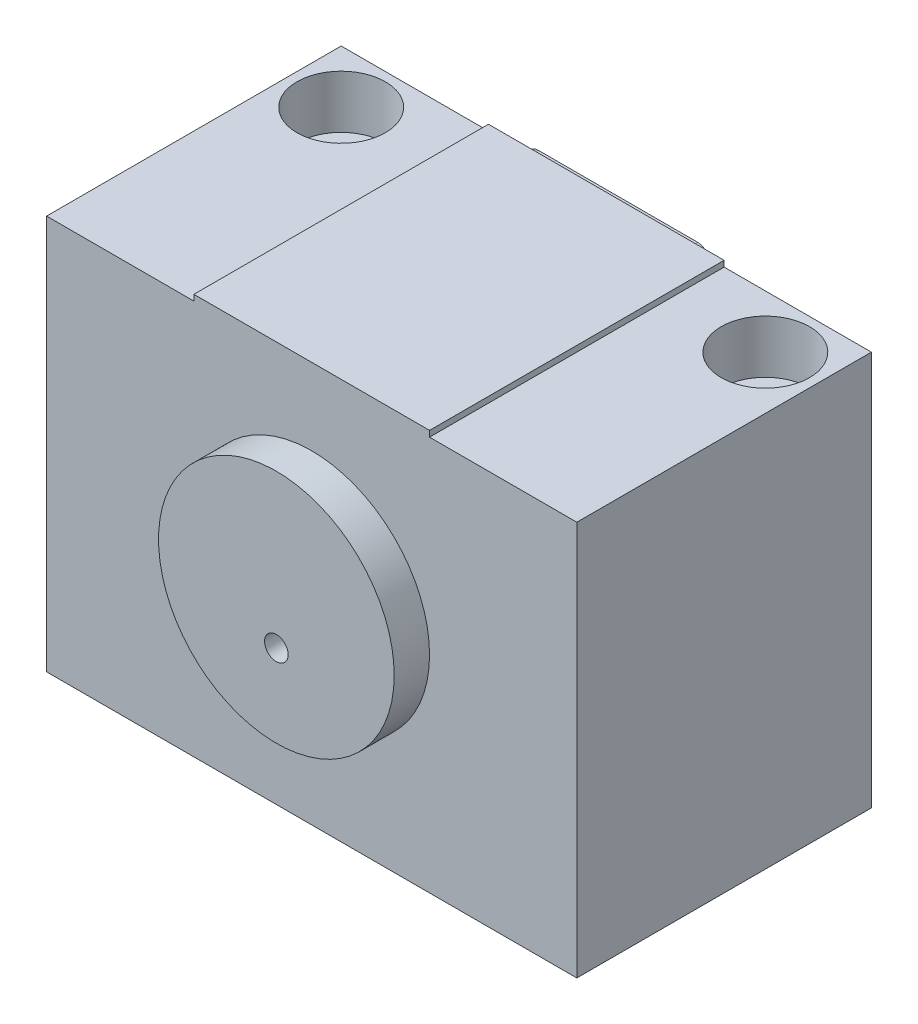
SolidWorks part; units mm, degrees
material "6061-O (SS)"
ref_plane "Plane1" through (0, 0, 0) normal (0, 0, 1) x (1, 0, 0)
ref_plane "Plane2" through (0, 0, 0) normal (0, 1, 0) x (1, 0, 0)
ref_plane "Plane3" through (0, 0, 0) normal (1, 0, 0) x (0, 0, -1)
sketch "Sketch1" plane through (0, 0, 0) normal (0, 0, 1) x (1, 0, 0)
  line L0 (0, 0) -> (0, 42.6415) construction
  line L1 (-22.5, 16) -> (22.5, 16)
  line L2 (-22.5, 16) -> (-22.5, -17.5)
  line L3 (-22.5, -17.5) -> (22.5, -17.5)
  line L4 (22.5, 16) -> (22.5, -17.5)
  line L5 (0, 0) -> (54.7738, 0) construction
  dimension "D1" = 45
  dimension "D2" = 17.5
  dimension "D3" = 33.5
extrude "Base-Extrude" add sketch "Sketch1" along normal blind 25
sketch "Sketch2" plane through (0, 0, 0) normal (0, 0, 1) x (1, 0, 0)
  line L0 (22.5, 16) -> (-22.5, 16) construction
  line L1 (-10, 16.5) -> (10, 16.5)
  line L2 (-10, 16.5) -> (-10, 16)
  line L3 (-10, 16) -> (10, 16)
  line L4 (10, 16.5) -> (10, 16)
  line L5 (0, 0) -> (0, 18.5769) construction
  dimension "D1" = 0.5
  dimension "D2" = 20
extrude "TopBoss" add sketch "Sketch2" along normal up to surface (25 mm away)
sketch "Sketch3" plane through (0, 0, 25) normal (0, 0, 1) x (1, 0, 0)
  circle A0 centre (0, 0) radius 10
  dimension "D1" = 20
extrude "Insert" add sketch "Sketch3" along normal blind 3
sketch "Sketch4" plane through (0, 0, 25) normal (0, 0, -1) x (-1, 0, 0)
  line L0 (22.5, -17.5) -> (-22.5, -17.5) construction
  line L1 (22.5, -17.5) -> (-22.5, -17.5)
  line L2 (-22.5, -16.5) -> (22.5, -16.5)
  line L3 (-22.5, -17.5) -> (-22.5, 16) construction
  line L4 (22.5, -16.5) -> (22.5, -17.5)
  line L5 (-22.5, -16.5) -> (-22.5, -17.5)
  dimension "D1" = 1
extrude "Flange" [suppressed] add sketch "Sketch4" along normal blind 1
sketch "Sketch13" [suppressed] plane through (0, -38, 0) normal (0, 1, 0) x (-1, 0, 0)
  line L0 (0, 0) -> (0, -89.7296) construction
  line L1 (70, -35) -> (-70, -35) construction
  circle A0 centre (-45, -20) radius 7
  circle A1 centre (45, -20) radius 7
  dimension "D1" = 14
  dimension "D2" = 15
  dimension "D3" = 90
extrude "FlangeMountHoles" [suppressed] cut sketch "Sketch13" against normal through all
sketch "Sketch5" plane through (0, 16, 0) normal (0, 1, 0) x (-1, 0, 0)
  line L0 (0, 0) -> (0, -8.6862) construction
  line L1 (0, 28) -> (0, 25) construction
  line L3 (-22.5, 25) -> (-10, 25) construction
  circle A0 centre (18, 4.5) radius 3.75
  circle A1 centre (-18, 4.5) radius 3.75
  dimension "D2" = 36
  dimension "D3" = 7.5
  dimension "D1" = 20.5
extrude "TopCbores" cut sketch "Sketch5" against normal blind 4.5
sketch "Sketch6" plane through (0, 11.5, 0) normal (0, 1, 0) x (-1, 0, 0)
  circle A0 centre (-18, 4.5) radius 2.25
  circle A1 centre (18, 4.5) radius 2.25
extrude "TopThruHoles" cut sketch "Sketch6" against normal through all
sketch "Sketch18" plane through (0, 0, 0) normal (1, 0, 0) x (0, 0, -1)
  line L0 (-25, -17.5) -> (-25, 16) construction
  line L1 (-25, -17.5) -> (0, -17.5) construction
  circle A0 centre (-12.5, 5) radius 1
  dimension "Diameter" = 2
  dimension "D3" = 12.5
  dimension "SidePort" = 22.5
extrude "PortThruHoleTop" cut sketch "Sketch18" against normal through all and the other way through all
sketch "Sketch24" plane through (22.5, 0, 0) normal (1, 0, 0) x (0, 0, -1)
  line L0 (-25, -17.5) -> (0, -17.5) construction
  line L1 (-25, -17.5) -> (-25, 16) construction
  circle A0 centre (-12.5, -6) radius 1
  dimension "D1" = 2
  dimension "SidePort" = 11.5
  dimension "D3" = 12.5
extrude "PortThruHoleBottom" cut sketch "Sketch24" against normal through all
sketch "Sketch7" plane through (0, 0, 0) normal (1, 0, 0) x (0, 0, -1)
  circle A0 centre (-12.5, 5) radius 2.5
  circle A2 centre (-12.5, 5) radius 1 construction
  dimension "PortDiameter" = 5
sketch "Sketch27" plane through (0, 0, 0) normal (1, 0, 0) x (0, 0, -1)
  circle A0 centre (-12.5, 5) radius 2.5
  circle A2 centre (-12.5, 5) radius 1 construction
  dimension "D1" = 5
sketch "Sketch25" plane through (22.5, 0, 0) normal (1, 0, 0) x (0, 0, -1)
  circle A0 centre (-12.5, 5) radius 2.5 construction
  circle A1 centre (-12.5, 5) radius 2.5
extrude "SideACboreTop" cut sketch "Sketch25" against normal blind 5
sketch "Sketch26" plane through (-22.5, 0, 0) normal (-1, 0, 0) x (0, 0, 1)
  circle A0 centre (12.5, 5) radius 2.5 construction
  circle A1 centre (12.5, 5) radius 2.5
extrude "SideBCboreTop" cut sketch "Sketch26" against normal blind 5
sketch "Sketch28" plane through (22.5, 0, 0) normal (1, 0, 0) x (0, 0, -1)
  circle A1 centre (-12.5, -6) radius 2.5
  circle A2 centre (-12.5, -6) radius 1 construction
  dimension "D1" = 5
extrude "SideACboreBottom" cut sketch "Sketch28" against normal blind 5
sketch "Sketch29" plane through (-22.5, 0, 0) normal (-1, 0, 0) x (0, 0, 1)
  circle A1 centre (12.5, -6) radius 2.5
  circle A2 centre (12.5, -6) radius 1 construction
  dimension "D1" = 5
extrude "SideBCboreBottom" cut sketch "Sketch29" against normal blind 5
sketch "Sketch16" plane through (22.5, 0, 0) normal (1, 0, 0) x (0, 0, -1)
  line L3 (-25, -17.5) -> (0, -17.5) construction
  line L4 (0, -17.5) -> (0, 16) construction
  circle A0 centre (-17.5, 0) radius 2.5
  dimension "D2" = 5
  dimension "D3" = 17.5
  dimension "D1" = 17.5
extrude "CushionValveCut" [suppressed] cut sketch "Sketch16" against normal blind 2
sketch "Sketch17" [suppressed] plane through (20.5, 0, 0) normal (1, 0, 0) x (0, 0, -1)
  circle A0 centre (-20.5, 0) radius 2
  dimension "D1" = 4
extrude "CushionValve" [suppressed] add sketch "Sketch17" along normal up to surface (2 mm away)
sketch "Sketch19" plane through (-22.5, 0, 0) normal (-1, 0, 0) x (0, 0, 1)
  line L0 (27.3913, 0) -> (108.5888, 0) construction
  line L1 (25, -17.5) -> (0, -17.5) construction
  line L2 (0, 16) -> (0, -17.5) construction
  circle A0 centre (17.5, 0) radius 2.5
  dimension "D1" = 17.5
  dimension "D2" = 5
  dimension "D3" = 17.5
extrude "CValveCut2" cut sketch "Sketch19" against normal blind 2
sketch "Sketch30" plane through (-20.5, 0, 0) normal (-1, 0, 0) x (0, 0, 1)
  circle A0 centre (17.5, 0) radius 2
  dimension "D1" = 4
extrude "CValve2" add sketch "Sketch30" along normal up to surface (2 mm away)
sketch "Sketch20" plane through (22.5, 0, 0) normal (1, 0, 0) x (0, 0, -1)
  circle A0 centre (-12.5, 5) radius 2.5 construction
  circle A1 centre (-12.5, 5) radius 2.5
extrude "1" add sketch "Sketch20" against normal blind 4
sketch "Sketch21" plane through (22.5, 0, 0) normal (1, 0, 0) x (0, 0, -1)
  circle A0 centre (-12.5, -6) radius 2.5 construction
  circle A1 centre (-12.5, -6) radius 2.5
extrude "2" add sketch "Sketch21" against normal blind 4
sketch "Sketch22" [suppressed] plane through (-22.5, 0, 0) normal (-1, 0, 0) x (0, 0, 1)
  circle A0 centre (12.5, -6) radius 2.5 construction
  circle A1 centre (12.5, -6) radius 2.5
extrude "3" [suppressed] add sketch "Sketch22" against normal blind 4
sketch "Sketch23" [suppressed] plane through (-22.5, 0, 0) normal (-1, 0, 0) x (0, 0, 1)
  circle A1 centre (12.5, 5) radius 2.5
  circle A2 centre (12.5, 5) radius 2.5 construction
extrude "4" [suppressed] add sketch "Sketch23" against normal blind 4
sketch "Sketch31" plane through (0, 0, 0) normal (0, 0, -1) x (-1, 0, 0)
  line L2 (-22.5, 16) -> (-10, 16) construction
  line L3 (0, 0) -> (0, 10.6501) construction
  circle A0 centre (0, 0) radius 2.5
  dimension "Port1Diameter" = 5
  dimension "D1" = 16
extrude "CenterEndPortH" [suppressed] cut sketch "Sketch31" against normal blind 5
sketch "Sketch34" [suppressed] plane through (0, 0, 5.2) normal (0, 0, -1) x (-1, 0, 0)
  circle A0 centre (0, 0) radius 1
  dimension "D1" = 2
extrude "CenterEndPortHThru" [suppressed] cut sketch "Sketch34" against normal through all
sketch "Sketch35" plane through (0, 0, 0) normal (0, 0, -1) x (-1, 0, 0)
  line L0 (-22.5, -17.5) -> (-22.5, 16) construction
  line L1 (-22.5, 16) -> (-10, 16) construction
  circle A0 centre (0, -3) radius 2.5
  dimension "PortDiameter" = 5
  dimension "SideIN" = 22.5
  dimension "TopDown" = 19
extrude "CenterEndPortH&R_G" cut sketch "Sketch35" against normal blind 5
sketch "Sketch36" plane through (0, 0, 5) normal (0, 0, -1) x (-1, 0, 0)
  circle A0 centre (0, -3) radius 1
  circle A1 centre (0, -3) radius 2.5 construction
  dimension "D1" = 2
extrude "CenterEndPortH&R_G_Thru" cut sketch "Sketch36" against normal through all
sketch "Sketch37" plane through (0, 0, 0) normal (0, 0, -1) x (-1, 0, 0)
  line L0 (-22.5, -17.5) -> (-22.5, 16) construction
  line L1 (-22.5, 16) -> (-10, 16) construction
  circle A0 centre (12, 2) radius 2.5
  dimension "PortDiameter" = 5
  dimension "EdgeIN" = 34.5
  dimension "TopDown" = 14
extrude "OffCenterEndPortH&R" cut sketch "Sketch37" against normal blind 5
sketch "Sketch38" plane through (0, 0, 5) normal (0, 0, -1) x (-1, 0, 0)
  circle A0 centre (12, 2) radius 1
  dimension "ThruDiameter" = 2
extrude "OffCenterEndPortH&RThru" cut sketch "Sketch38" against normal blind 5
sketch "Sketch39" plane through (0, 0, 0) normal (0, 0, -1) x (-1, 0, 0)
  line L0 (-6.75, 15.7) -> (6.75, 15.7)
  line L1 (7.75, 13.2) -> (5.1519, 8.7)
  line L2 (5.1519, 8.7) -> (-5.1519, 8.7)
  line L3 (-5.1519, 8.7) -> (-7.75, 13.2)
  line L4 (0, 0) -> (0, 15.5631) construction
  line L5 (10, 16) -> (22.5, 16) construction
  line L6 (7.75, 13.2) -> (7.75, 14.7)
  line L7 (-7.75, 13.2) -> (-7.75, 14.7)
  arc A0 (-7.75, 14.7) -> (-6.75, 15.7) centre (-6.75, 14.7) cw
  arc A1 (7.75, 14.7) -> (6.75, 15.7) centre (6.75, 14.7) ccw
  point P13 (-7.75, 15.7)
  point P16 (7.75, 15.7)
  dimension "D1" = 1
  dimension "D2" = 15.5
  dimension "D3" = 120
  dimension "D4" = 7
  dimension "D5" = 0.3
  dimension "D6" = 2.5
extrude "PlasticCap" add sketch "Sketch39" along normal blind 1
sketch "Sketch40" plane through (0, -17.5, 0) normal (0, -1, 0) x (1, 0, 0)
  line L0 (0, 0) -> (0, 37.3904) construction
  line L1 (-22.5, 25) -> (22.5, 25) construction
  circle A0 centre (12, 12.5) radius 2.5
  circle A1 centre (-12, 12.5) radius 2.5
  dimension "D1" = 12.5
  dimension "D2" = 5
  dimension "XX" = 24
extrude "BottomPorts" cut sketch "Sketch40" against normal blind 5
sketch "Sketch41" plane through (0, -17.5, 0) normal (0, -1, 0) x (1, 0, 0)
  circle A0 centre (12, 12.5) radius 1
  dimension "D1" = 2
extrude "BottomAPassage" cut sketch "Sketch41" against normal blind 22.5
sketch "Sketch42" plane through (0, -17.5, 0) normal (0, -1, 0) x (1, 0, 0)
  circle A0 centre (-12, 12.5) radius 1
  circle A1 centre (-12, 12.5) radius 2.5 construction
  dimension "D1" = 2
extrude "BottomBPassage" cut sketch "Sketch42" against normal blind 11.5
sketch "Sketch43" plane through (0, -17.5, 0) normal (0, -1, 0) x (1, 0, 0)
  circle A0 centre (-18, 4.5) radius 3
  circle A1 centre (-18, 4.5) radius 2.25 construction
  circle A2 centre (18, 4.5) radius 3
  circle A3 centre (18, 4.5) radius 2.25 construction
  dimension "D1" = 6
extrude "Cut-Extrude1" cut sketch "Sketch43" against normal blind 12
